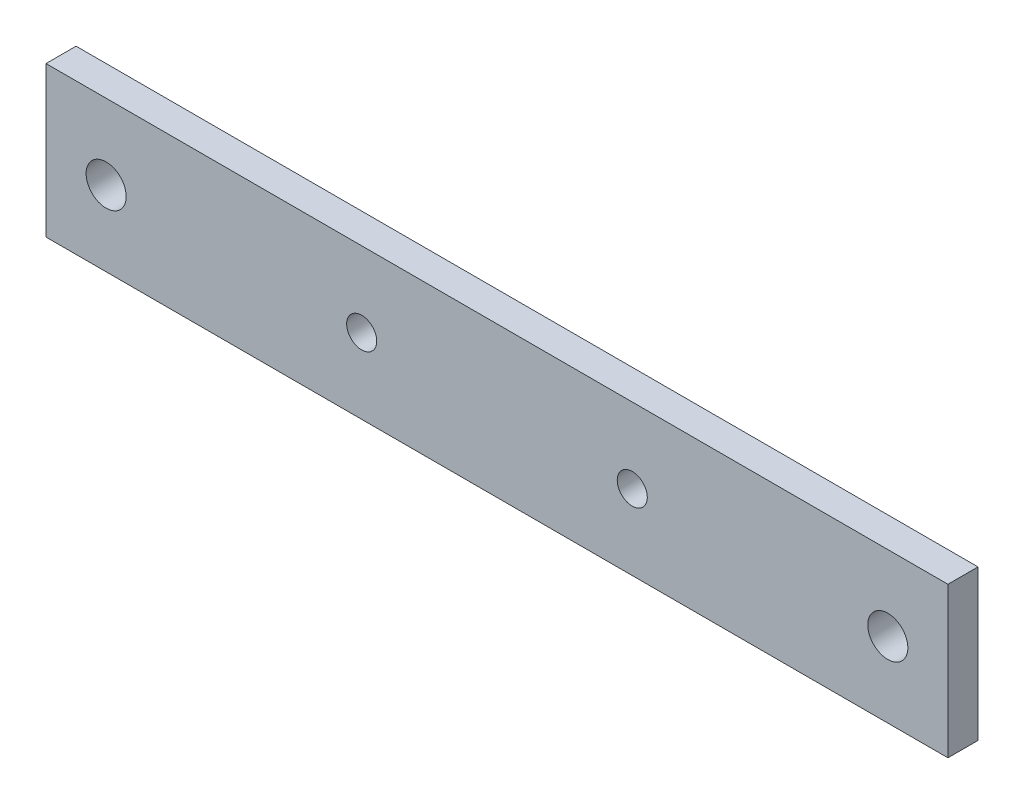
SolidWorks part; units mm, degrees
ref_plane "前视基准面" through (0, 0, 0) normal (0, 0, 1) x (1, 0, 0)
ref_plane "上视基准面" through (0, 0, 0) normal (0, 1, 0) x (1, 0, 0)
ref_plane "右视基准面" through (0, 0, 0) normal (1, 0, 0) x (0, 0, -1)
sketch "草图1" plane through (0, 0, 0) normal (0, 0, 1) x (1, 0, 0)
  line L0 (0, 7.5) -> (0, -7.5) construction
  line L1 (45, -7.5) -> (-45, -7.5)
  line L2 (45, -7.5) -> (45, 7.5)
  line L3 (45, 7.5) -> (-45, 7.5)
  line L4 (-45, -7.5) -> (-45, 7.5)
  line L5 (45, -7.5) -> (-45, 7.5) construction
  line L6 (45, 7.5) -> (-45, -7.5) construction
  line L7 (-45, 0) -> (45, 0) construction
  circle A0 centre (-13.5, 0) radius 1.5
  circle A1 centre (13.5, 0) radius 1.5
  circle A2 centre (-39, 0) radius 2
  circle A3 centre (39, 0) radius 2
  point P0 (0, 0)
  dimension "D3" = 3
  dimension "D5" = 4
  dimension "D1" = 15
  dimension "D2" = 90
  dimension "D4" = 13.5
  dimension "D6" = 39
extrude "凸台-拉伸1" add sketch "草图1" along normal blind 3
